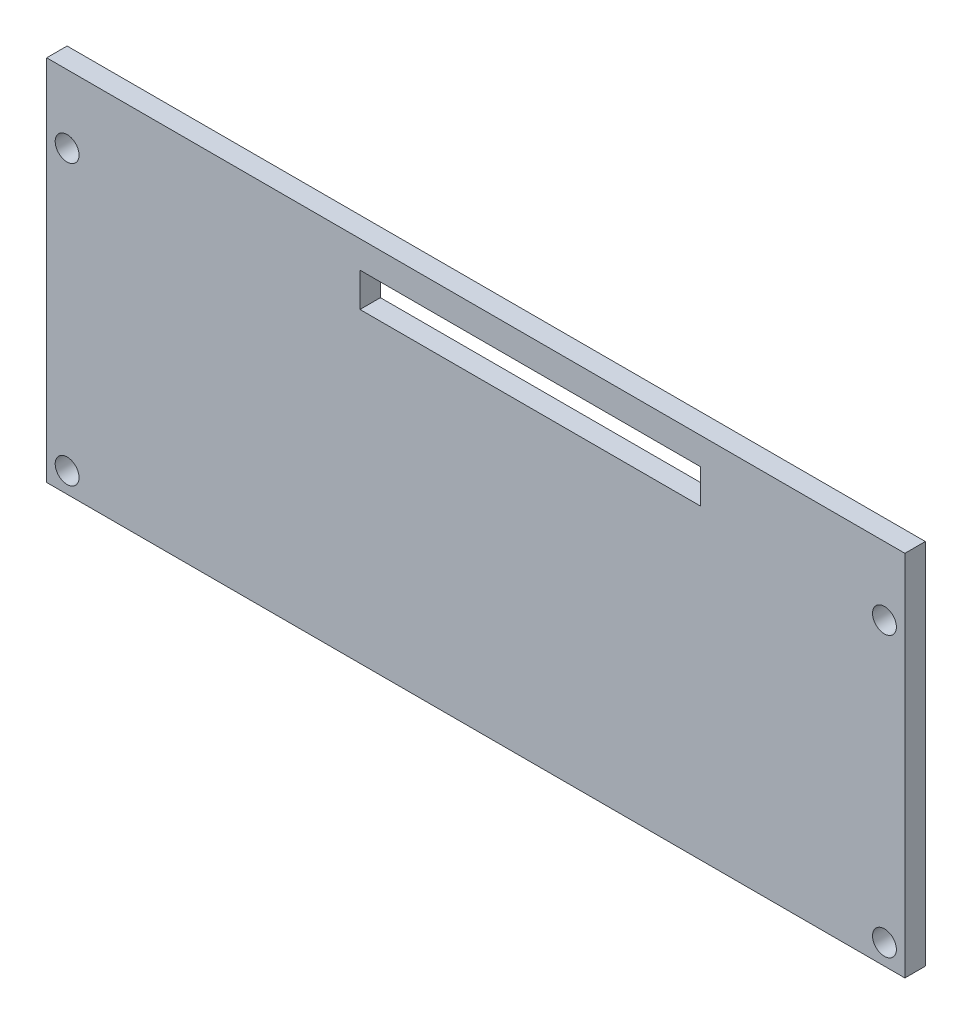
SolidWorks part; units mm, degrees
ref_plane "Front Plane" through (0, 0, 0) normal (0, 0, 1) x (1, 0, 0)
ref_plane "Top Plane" through (0, 0, 0) normal (0, 1, 0) x (1, 0, 0)
ref_plane "Right Plane" through (0, 0, 0) normal (1, 0, 0) x (0, 0, -1)
sketch "Sketch1" plane through (0, 0, 0) normal (0, 0, 1) x (1, 0, 0)
  line L0 (-17, 21) -> (33, 21)
  line L1 (-17, 25) -> (33, 25)
  line L2 (55, 0) -> (-55, 0) construction
  line L3 (-63, 25) -> (63, 25)
  line L4 (-63, 25) -> (-63, -29)
  line L5 (-63, -29) -> (63, -29)
  line L6 (63, 25) -> (63, -29)
  line L7 (0, -55) -> (0, 55) construction
  line L8 (-17, 21) -> (-17, 16)
  line L9 (-17, 16) -> (33, 16)
  line L10 (33, 21) -> (33, 16)
  circle A0 centre (-60, 15) radius 1.75
  circle A1 centre (60, 15) radius 1.75
  circle A2 centre (60, -26) radius 1.75
  circle A3 centre (-60, -26) radius 1.75
  dimension "D5" = 3.5
  dimension "D1" = 54
  dimension "D2" = 25
  dimension "D3" = 126
  dimension "D4" = 63
  dimension "D6" = 10
  dimension "D7" = 3
  dimension "D10" = 3
  dimension "D11" = 30
  dimension "D12" = 50
  dimension "D13" = 5
  dimension "D14" = 4
  dimension "D8" = 2
  dimension "D9" = 2
extrude "Boss-Extrude1" add sketch "Sketch1" along normal blind 3 contours L3 L10 L9 L8 L4 L5 L6 A3 A2 A1 A0
